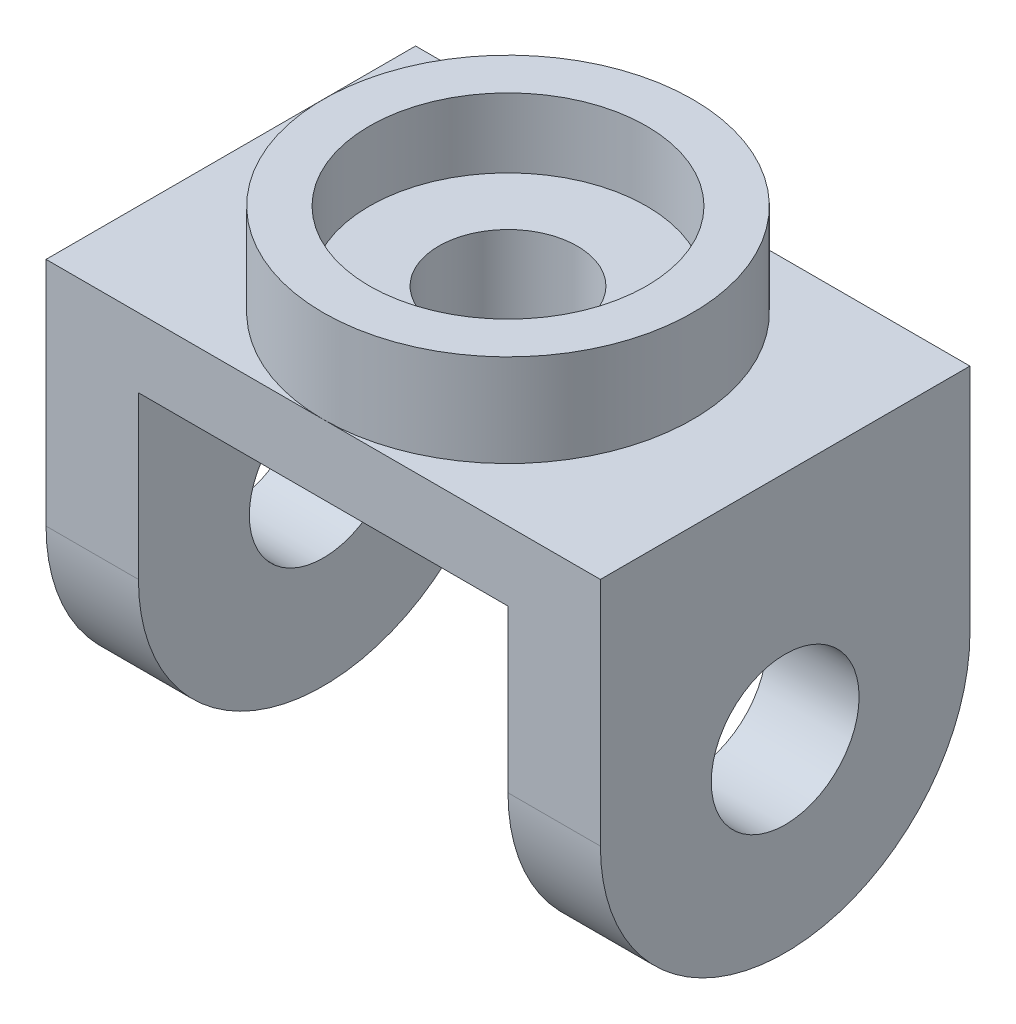
SolidWorks part; units mm, degrees
ref_plane "Front Plane" through (0, 0, 0) normal (0, 0, 1) x (1, 0, 0)
ref_plane "Top Plane" through (0, 0, 0) normal (0, 1, 0) x (1, 0, 0)
ref_plane "Right Plane" through (0, 0, 0) normal (1, 0, 0) x (0, 0, -1)
sketch "Sketch1" plane through (0, 0, 0) normal (0, 1, 0) x (1, 0, 0)
  line L1 (-60, 40) -> (60, 40)
  line L2 (-60, 40) -> (-60, -40)
  line L3 (-60, -40) -> (60, -40)
  line L4 (60, 40) -> (60, -40)
  line L5 (-60, 40) -> (60, -40) construction
  line L6 (-60, -40) -> (60, 40) construction
  point P0 (0, 0)
  dimension "D1" = 80
  dimension "D2" = 120
extrude "Boss-Extrude1" add sketch "Sketch1" along normal blind 15
sketch "Sketch2" plane through (0, 15, 0) normal (0, 1, 0) x (1, 0, 0)
  circle A0 centre (0, 0) radius 30
  circle A1 centre (0, 0) radius 40
  dimension "D1" = 60
  dimension "D2" = 80
extrude "Boss-Extrude2" add sketch "Sketch2" along normal blind 20
sketch "Sketch3" plane through (0, 15, 0) normal (0, 1, 0) x (1, 0, 0)
  circle A0 centre (0, 0) radius 30
  dimension "D1" = 60
extrude "Boss-Extrude3" add sketch "Sketch3" along normal blind 5
sketch "Sketch4" plane through (0, 20, 0) normal (0, 1, 0) x (1, 0, 0)
  circle A0 centre (0, 0) radius 15
  dimension "D1" = 30
extrude "Cut-Extrude1" cut sketch "Sketch4" against normal through all
sketch "Sketch6" plane through (-60, 0, 0) normal (-1, 0, 0) x (0, 0, 1)
  line L1 (-40, 15) -> (40, 15)
  line L2 (-40, 15) -> (-40, -35)
  line L4 (40, 15) -> (40, -35)
  arc A0 (-40, -35) -> (40, -35) centre (0, -35) ccw
  dimension "D3" = 80
  dimension "D1" = 80
  dimension "D2" = 50
extrude "Boss-Extrude6" add sketch "Sketch6" against normal blind 20 contours L4 A0 L2 L1
sketch "Sketch7" plane through (-60, 0, 0) normal (-1, 0, 0) x (0, 0, 1)
  line L0 (40, 15) -> (-40, 15) construction
  line L1 (40, 15) -> (40, -35) construction
  circle A0 centre (0, -35) radius 16
  dimension "D1" = 32
  dimension "D2" = 50
  dimension "D3" = 40
extrude "Cut-Extrude2" cut sketch "Sketch7" against normal up to next
mirror "Mirror2" about plane through (0, 0, 0) normal (1, 0, 0) of "Boss-Extrude1", "Boss-Extrude6", "Cut-Extrude2"
sketch "Sketch8" plane through (0, 15, 0) normal (0, 1, 0) x (1, 0, 0)
  circle A0 centre (0, 0) radius 15
  dimension "D1" = 30
extrude "Cut-Extrude3" cut sketch "Sketch8" against normal up to next
